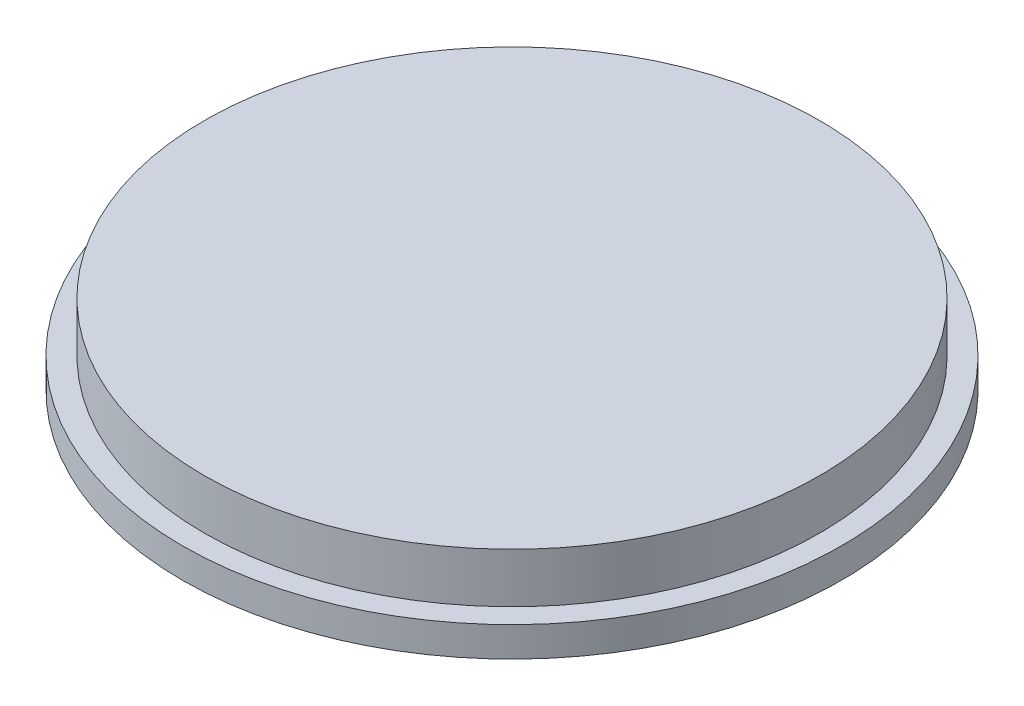
SolidWorks part; units mm, degrees
ref_plane "Front Plane" through (0, 0, 0) normal (0, 0, 1) x (1, 0, 0)
ref_plane "Top Plane" through (0, 0, 0) normal (0, 1, 0) x (1, 0, 0)
ref_plane "Right Plane" through (0, 0, 0) normal (1, 0, 0) x (0, 0, -1)
sketch "Sketch1" plane through (0, 0, 0) normal (0, 1, 0) x (1, 0, 0)
  circle A0 centre (0, 0) radius 33.1
  dimension "D1" = 66.2
extrude "Boss-Extrude1" add sketch "Sketch1" along normal blind 3
sketch "Sketch2" plane through (0, 3, 0) normal (0, 1, 0) x (1, 0, 0)
  circle A0 centre (0, 0) radius 30.9
  dimension "D1" = 61.8
extrude "Boss-Extrude2" add sketch "Sketch2" along normal blind 5
